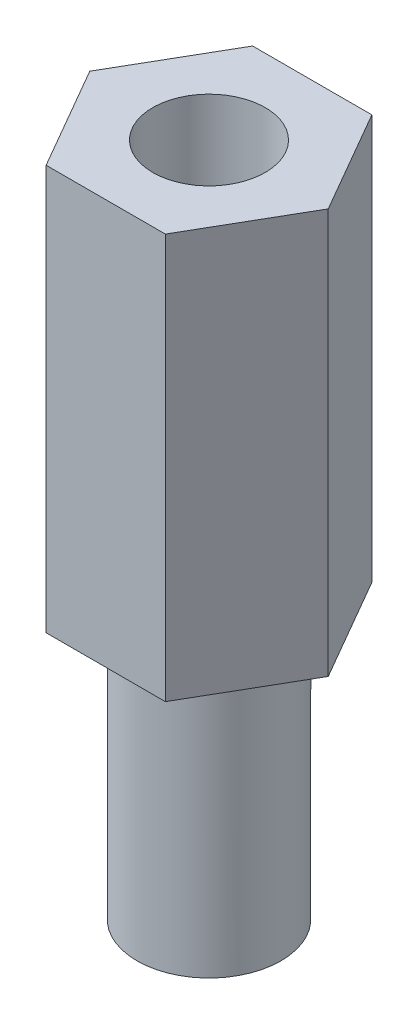
SolidWorks part; units mm, degrees
ref_plane "前视基准面" through (0, 0, 0) normal (0, 0, 1) x (1, 0, 0)
ref_plane "上视基准面" through (0, 0, 0) normal (0, 1, 0) x (1, 0, 0)
ref_plane "右视基准面" through (0, 0, 0) normal (1, 0, 0) x (0, 0, -1)
sketch "草图4" plane through (0, 0, 0) normal (0, 1, 0) x (1, 0, 0)
  line L0 (-12.7945, 0) -> (16.3015, 0) construction
  line L2 (1.325, -2.295) -> (2.65, 0)
  line L3 (2.65, 0) -> (1.325, 2.295)
  line L4 (1.325, 2.295) -> (-1.325, 2.295)
  line L5 (-1.325, 2.295) -> (-2.65, 0)
  line L6 (-2.65, 0) -> (-1.325, -2.295)
  line L7 (-1.325, -2.295) -> (1.325, -2.295)
  circle A0 centre (0, 0) radius 2.295 construction
  dimension "D1" = 5.3
extrude "凸台-拉伸1" add sketch "草图4" along normal blind 9
sketch "草图6" plane through (0, 0, 0) normal (0, -1, 0) x (-1, 0, 0)
  circle A0 centre (0, 0) radius 1.6
  dimension "D1" = 3.2
extrude "凸台-拉伸2" add sketch "草图6" along normal blind 6
cosmetic thread "装饰螺纹线1" parameters "D2"=2.5
sketch "草图7" plane through (0, 9, 0) normal (0, 1, 0) x (1, 0, 0)
  circle A0 centre (0, 0) radius 1.25
  dimension "D1" = 2.5
extrude "切除-拉伸1" cut sketch "草图7" against normal blind 5
cosmetic thread "装饰螺纹线2" parameters "D2"=3
